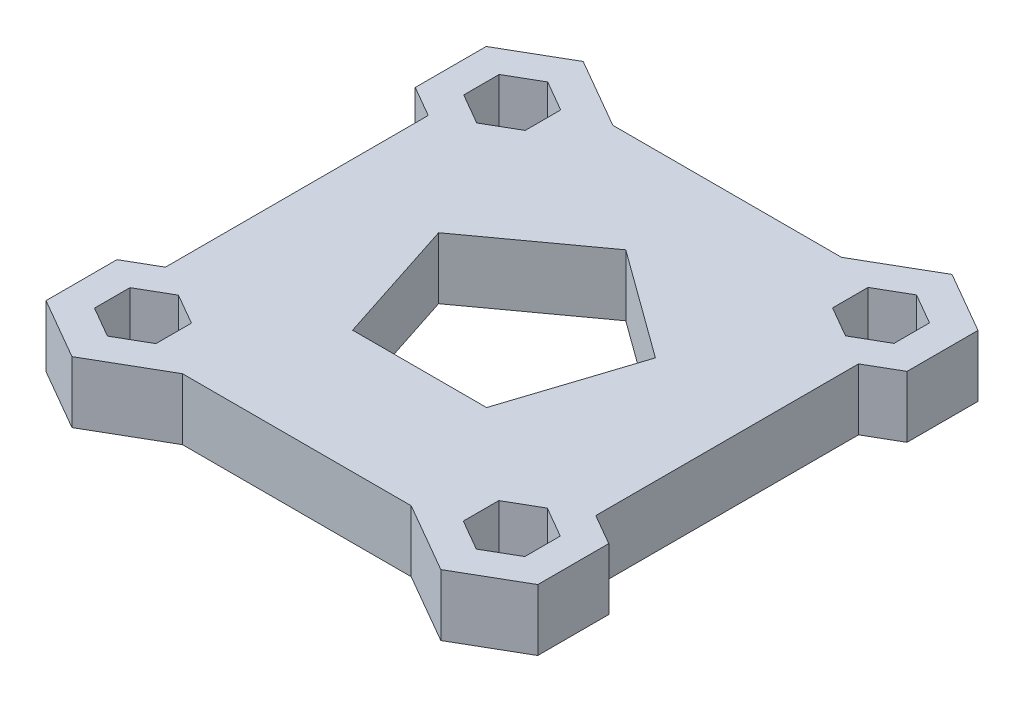
SolidWorks part; units mm, degrees
ref_plane "Front Plane" through (0, 0, 0) normal (0, 0, 1) x (1, 0, 0)
ref_plane "Top Plane" through (0, 0, 0) normal (0, 1, 0) x (1, 0, 0)
ref_plane "Right Plane" through (0, 0, 0) normal (1, 0, 0) x (0, 0, -1)
sketch "Sketch2" plane through (0, 0, 0) normal (0, 1, 0) x (1, 0, 0)
  line L48 (-23.6259, 44.4919) -> (23.6259, 44.4919)
  line L49 (-38.1, 52.8485) -> (-50.8, 45.5162)
  line L50 (-50.8, 45.5162) -> (-50.8, 30.8515)
  line L51 (-50.8, 30.8515) -> (-44.45, 27.1853)
  line L54 (-23.6259, 44.4919) -> (-38.1, 52.8485)
  line L55 (38.1, 52.8485) -> (23.6259, 44.4919)
  line L63 (44.45, 27.1853) -> (50.8, 30.8515)
  line L64 (50.8, 30.8515) -> (50.8, 45.5162)
  line L65 (50.8, 45.5162) -> (38.1, 52.8485)
  line L66 (-44.45, -27.1015) -> (-50.8, -30.7677)
  line L67 (-50.8, -30.7677) -> (-50.8, -45.4323)
  line L68 (-50.8, -45.4323) -> (-38.1, -52.7647)
  line L69 (-38.1, -52.7647) -> (-23.6259, -44.4081)
  line L74 (23.6259, -44.4081) -> (38.1, -52.7647)
  line L75 (38.1, -52.7647) -> (50.8, -45.4323)
  line L76 (50.8, -45.4323) -> (50.8, -30.7677)
  line L77 (50.8, -30.7677) -> (44.45, -27.1015)
  line L79 (-23.6259, -44.4081) -> (23.6259, -44.4081)
  line L80 (44.45, 27.1853) -> (44.45, -27.1015)
  line L82 (-37.8315, 23.6741) -> (-21.1162, 33.3247) [skipped]
  line L83 (-25.4, 38.2322) -> (-25.4, 47.8828) [skipped]
  line L84 (-41.3962, -21.5322) -> (-49.3978, -16.9125) [skipped]
  line L85 (-25.4, -51.5231) -> (-25.4, -42.2837) [skipped]
  line L86 (41.3516, 21.6418) -> (49.7093, 16.8165) [skipped]
  line L87 (25.4, 50.3654) -> (25.4, 40.7149) [skipped]
  line L88 (43.3748, -20.3899) -> (35.3732, -25.0096) [skipped]
  line L89 (25.4, -48.5916) -> (25.4, -57.831) [skipped]
  line L90 (-44.45, 27.1853) -> (-44.45, -27.1015)
  line L92 (-38.1, 45.5162) -> (-44.45, 41.85)
  line L93 (-44.45, 41.85) -> (-44.45, 34.5176)
  line L94 (-44.45, 34.5176) -> (-38.1, 30.8515)
  line L95 (-38.1, 30.8515) -> (-31.75, 34.5176)
  line L96 (-31.75, 34.5176) -> (-31.75, 41.85)
  line L97 (-31.75, 41.85) -> (-38.1, 45.5162)
  line L98 (38.1, 45.5162) -> (31.75, 41.85)
  line L99 (31.75, 41.85) -> (31.75, 34.5176)
  line L100 (31.75, 34.5176) -> (38.1, 30.8515)
  line L101 (38.1, 30.8515) -> (44.45, 34.5176)
  line L102 (44.45, 34.5176) -> (44.45, 41.85)
  line L103 (44.45, 41.85) -> (38.1, 45.5162)
  line L104 (-38.1, -30.7677) -> (-44.45, -34.4338)
  line L105 (-44.45, -34.4338) -> (-44.45, -41.7662)
  line L106 (-44.45, -41.7662) -> (-38.1, -45.4323)
  line L107 (-38.1, -45.4323) -> (-31.75, -41.7662)
  line L108 (-31.75, -41.7662) -> (-31.75, -34.4338)
  line L109 (-31.75, -34.4338) -> (-38.1, -30.7677)
  line L110 (38.1, -30.7677) -> (31.75, -34.4338)
  line L111 (31.75, -34.4338) -> (31.75, -41.7662)
  line L112 (31.75, -41.7662) -> (38.1, -45.4323)
  line L113 (38.1, -45.4323) -> (44.45, -41.7662)
  line L114 (44.45, -41.7662) -> (44.45, -34.4338)
  line L115 (44.45, -34.4338) -> (38.1, -30.7677)
  line L116 (0, 23.5471) -> (-22.3946, 7.2765)
  line L117 (-22.3946, 7.2765) -> (-13.8406, -19.05)
  line L118 (-13.8406, -19.05) -> (13.8406, -19.05)
  line L119 (13.8406, -19.05) -> (22.3946, 7.2765)
  line L120 (22.3946, 7.2765) -> (0, 23.5471)
  arc A0 (-31.75, 49.1823) -> (-44.45, 27.1853) centre (-38.1, 38.1838) ccw construction
  arc A1 (44.45, 27.1853) -> (31.75, 49.1823) centre (38.1, 38.1838) ccw construction
  arc A2 (-44.45, -27.1015) -> (-31.75, -49.0985) centre (-38.1, -38.1) ccw construction
  arc A3 (31.75, -49.0985) -> (44.45, -27.1015) centre (38.1, -38.1) ccw construction
  circle A4 centre (-38.1, 38.1838) radius 6.35 construction
  circle A5 centre (38.1, 38.1838) radius 6.35 construction
  circle A6 centre (-38.1, -38.1) radius 6.35 construction
  circle A7 centre (38.1, -38.1) radius 6.35 construction
  circle A8 centre (0, 0) radius 19.05 construction
  point P18 (38.1, 52.7881)
  point P59 (0, 0)
  point P66 (0, 0)
  point P67 (0, 0)
  point P68 (0, 0)
  point P69 (0, 0)
  point P70 (0, 0)
  point P71 (39.0071, -8.9614)
  point P72 (0, 0)
  point P73 (0, 0)
  point P74 (0, 0)
  point P75 (0, 0)
  point P76 (0, 0)
  point P77 (0, 0)
  point P78 (0, 0)
  point P79 (0, 0)
  point P80 (0, 0)
  point P81 (0, 0)
  point P82 (0, 44.4919)
  point P83 (0, 0)
  point P84 (0, 0)
  point P85 (0, 0)
  point P86 (0, 0)
  point P87 (0, 0)
  point P88 (0, 0)
  point P89 (0, 0)
  point P90 (0, 0)
  point P91 (0, 0)
  point P92 (0, 0)
  point P109 (0, 0)
  point P110 (38.1, -30.7677)
  point P111 (-38.1, -30.7677)
  point P112 (38.1, -30.7677)
  point P113 (0, 0)
  point P114 (-117.331, 40.6403)
  point P116 (0, 0)
  point P118 (-38.1, 52.7881)
  point P119 (0, 0)
  point P120 (0, 0)
  point P121 (0, 0)
  point P122 (0, 0)
  dimension "D3" = 38.1
  dimension "D4" = 76.2
  dimension "D1" = 12.7
  dimension "D2" = 12.7
  dimension "D7" = 38.1
  dimension "D5" = 38.1
  dimension "D6" = 88.9
  dimension "D8" = 76.2838
extrude "Boss-Extrude1" add sketch "Sketch2" along normal blind 12.7
